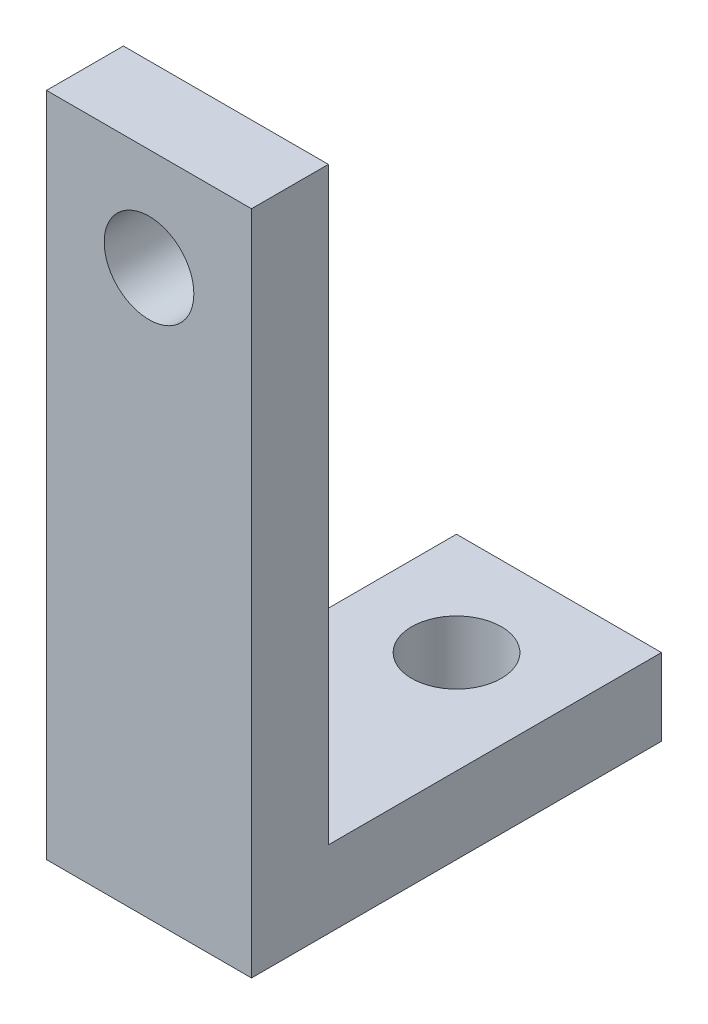
SolidWorks part; units mm, degrees
ref_plane "Front Plane" through (0, 0, 0) normal (0, 0, 1) x (1, 0, 0)
ref_plane "Top Plane" through (0, 0, 0) normal (0, 1, 0) x (1, 0, 0)
ref_plane "Right Plane" through (0, 0, 0) normal (1, 0, 0) x (0, 0, -1)
sketch "Sketch1" plane through (0, 0, 0) normal (0, 0, 1) x (1, 0, 0)
  line L1 (-52.2175, 20.1569) -> (-44.2175, 20.1569)
  line L2 (-52.2175, 20.1569) -> (-52.2175, -5.8431)
  line L3 (-52.2175, -5.8431) -> (-44.2175, -5.8431)
  line L4 (-44.2175, 20.1569) -> (-44.2175, -5.8431)
extrude "Boss-Extrude1" add sketch "Sketch1" along normal blind 3
sketch "Sketch2" plane through (0, 0, 0) normal (0, 0, -1) x (-1, 0, 0)
  line L0 (52.2175, -5.8431) -> (44.2175, -5.8431)
  line L1 (44.2175, -5.8431) -> (44.2175, -2.8431)
  line L2 (44.2175, -5.8431) -> (44.2175, 20.1569) construction
  line L3 (44.2175, -2.8431) -> (52.2175, -2.8431)
  line L4 (52.2175, 20.1569) -> (52.2175, -5.8431) construction
  line L5 (52.2175, -2.8431) -> (52.2175, -5.8431)
extrude "Boss-Extrude2" add sketch "Sketch2" along normal blind 13
sketch "Sketch3" plane through (0, -5.8431, 0) normal (0, -1, 0) x (-1, 0, 0)
  circle A0 centre (48.2175, 9) radius 1.75
extrude "Cut-Extrude1" cut sketch "Sketch3" against normal blind 8
sketch "Sketch4" plane through (0, 0, 3) normal (0, 0, 1) x (1, 0, 0)
  circle A0 centre (-48.2175, 16.1569) radius 1.75
extrude "Cut-Extrude2" cut sketch "Sketch4" against normal blind 8
